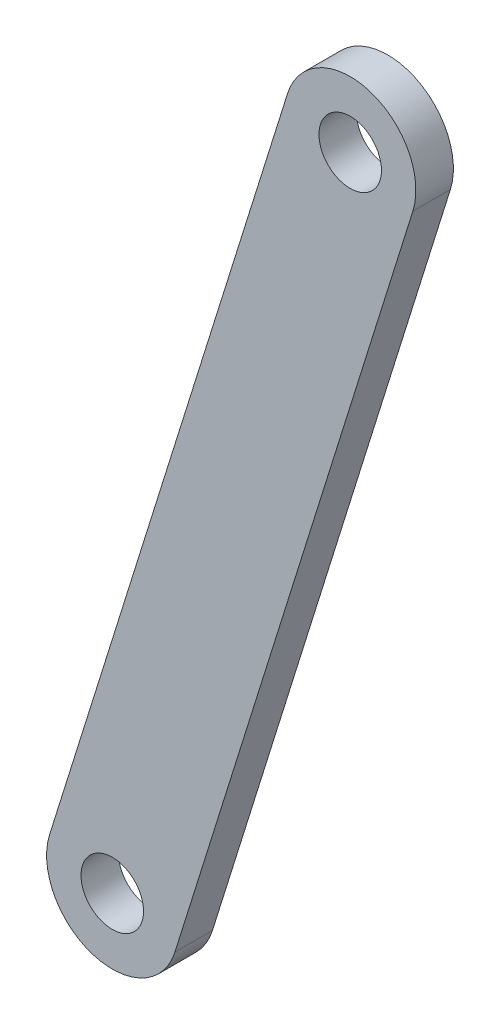
SolidWorks part; units mm, degrees
ref_plane "Front Plane" through (0, 0, 0) normal (0, 0, 1) x (1, 0, 0)
ref_plane "Top Plane" through (0, 0, 0) normal (0, 1, 0) x (1, 0, 0)
ref_plane "Right Plane" through (0, 0, 0) normal (1, 0, 0) x (0, 0, -1)
sketch "Sketch1" plane through (0, 0, 0) normal (0, 0, 1) x (1, 0, 0)
  line L0 (12.3859, 41.1827) -> (-6.6398, -19.6436)
  line L1 (3.3814, -22.7781) -> (22.4071, 38.0482)
  arc A0 (12.3859, 41.1827) -> (22.4071, 38.0482) centre (17.3965, 39.6155) cw
  circle A1 centre (17.3965, 39.6155) radius 2.5
  arc A2 (-6.6398, -19.6436) -> (3.3814, -22.7781) centre (-1.6292, -21.2108) ccw
  circle A3 centre (-1.6292, -21.2108) radius 2.5
  dimension "D2" = 5.25
  dimension "D3" = 5
  dimension "D4" = 5
  dimension "D5" = 5.25
  dimension "D1" = 63.7324
extrude "Boss-Extrude1" add sketch "Sketch1" along normal blind 3
